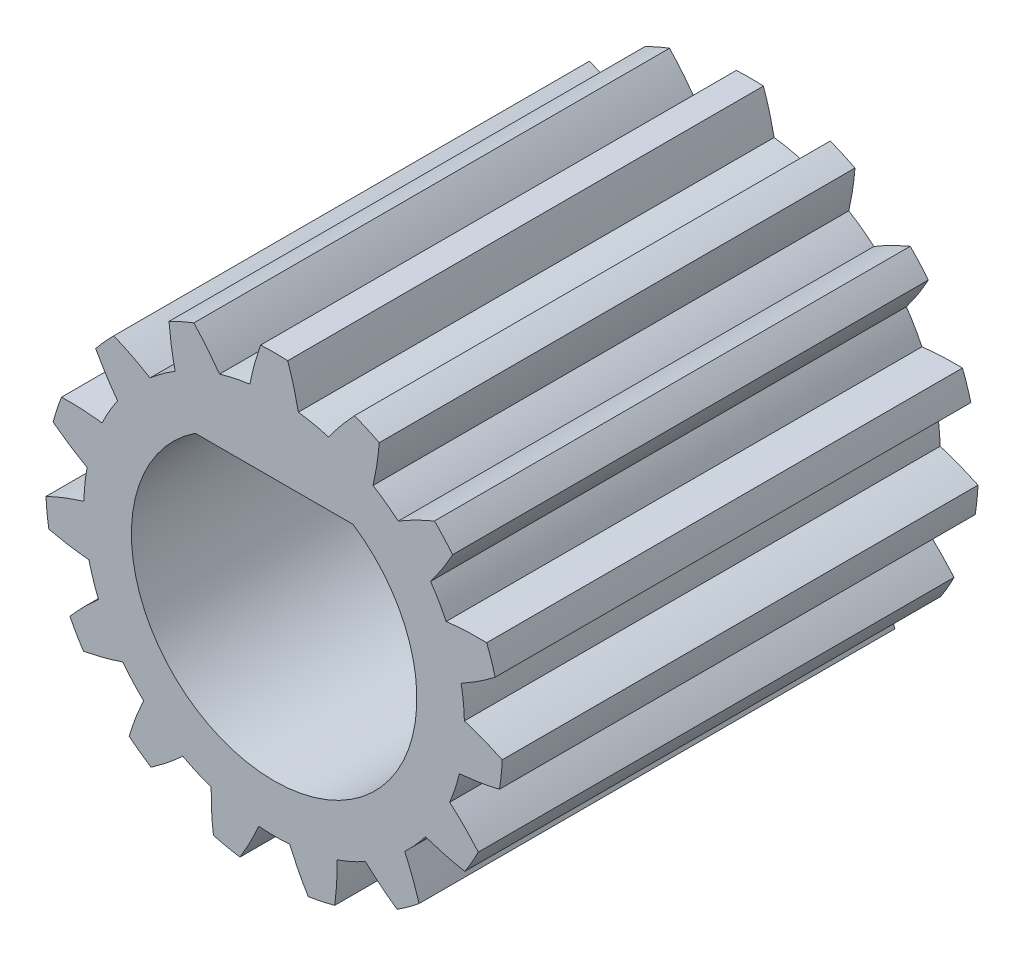
SolidWorks part; units mm, degrees
ref_plane "Front Plane" through (0, 0, 0) normal (0, 0, 1) x (1, 0, 0)
ref_plane "Top Plane" through (0, 0, 0) normal (0, 1, 0) x (1, 0, 0)
ref_plane "Right Plane" through (0, 0, 0) normal (1, 0, 0) x (0, 0, -1)
sketch "Sketch1" plane through (0, 0, 0) normal (0, 0, 1) x (1, 0, 0)
  line L0 (-1.6583, 2.5) -> (1.6583, 2.5)
  arc A0 (-1.6583, 2.5) -> (1.6583, 2.5) centre (0, 0) ccw
  circle A1 centre (0, 0) radius 4
  dimension "D1" = 6
  dimension "D3" = 8
  dimension "D2" = 2.5
extrude "Boss-Extrude1" add sketch "Sketch1" along normal mid plane 10
sketch "Sketch2" plane through (0, 0, 0) normal (0, 0, 1) x (1, 0, 0)
  line L0 (0, 0) -> (0, 9.3958) construction
  line L1 (0, 0) -> (-1.5091, 7.0998) construction
  line L2 (0, 0) -> (1.5278, 7.1878) construction
  circle A1 centre (0, 0) radius 4 construction
  arc A2 (0.2848, 4.7915) -> (-0.2848, 4.7915) centre (0, 0) ccw
  arc A7 (0.5094, 3.9674) -> (-0.5094, 3.9674) centre (0, 0) ccw
  spline S0 degree 2 poles (-0.2848, 4.7915) (-0.4274, 4.3877) (-0.5094, 3.9674) knots 0 0 0 1 1 1
  spline S1 degree 2 poles (0.2848, 4.7915) (0.4274, 4.3877) (0.5094, 3.9674) knots 0 0 0 1 1 1
  dimension "D3" = 4.8
  dimension "D1" = 12
  dimension "D2" = 12
extrude "Boss-Extrude2" add sketch "Sketch2" along normal mid plane 10
pattern_circular "CirPattern1" count 15 over 360 about axis through (0, 0, 5) along (0, 0, -1) of "Boss-Extrude2"
